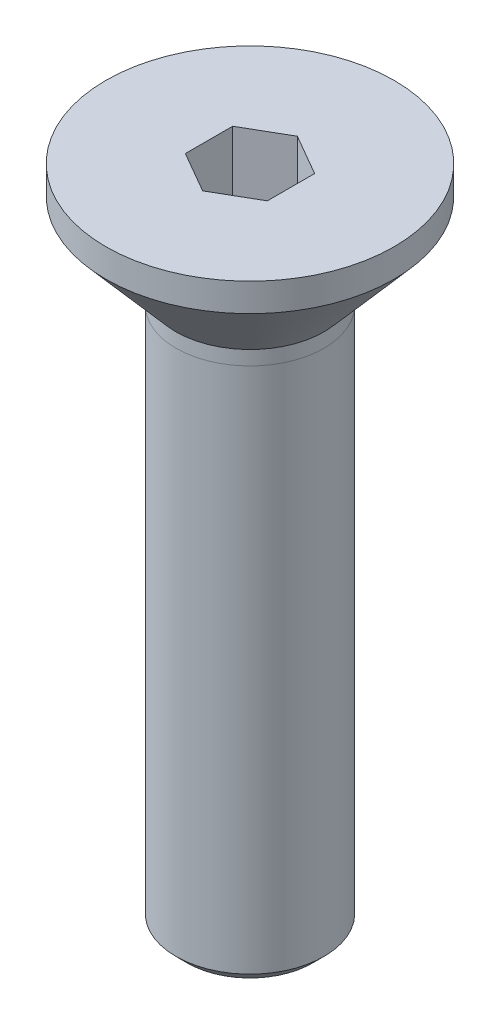
SolidWorks part; units mm, degrees
material "SS 18-8"
ref_plane "Front" through (0, 0, 0) normal (0, 0, 1) x (1, 0, 0)
ref_plane "Top" through (0, 0, 0) normal (0, 1, 0) x (1, 0, 0)
ref_plane "Right" through (0, 0, 0) normal (1, 0, 0) x (0, 0, -1)
sketch "Sketch1" plane through (0, 0, 0) normal (0, 0, 1) x (1, 0, 0)
  line L0 (0, 0) -> (0, -12.7)
  line L1 (0, -12.7) -> (1.2036, -12.7)
  line L2 (1.2036, -12.7) -> (1.4224, -12.4812)
  line L3 (1.4224, -12.4812) -> (1.4224, -2.0892)
  line L4 (0, 0) -> (2.7686, 0)
  line L5 (2.7686, 0) -> (2.7686, -0.5406)
  line L6 (2.7686, -0.5406) -> (1.4224, -2.0892)
  line L7 (2.7686, -0.5406) -> (3.2385, 0) construction
  line L8 (0, 0) -> (0, -25.4) construction
  line L9 (3.2385, 0) -> (2.7686, 0) construction
  dimension "D1" = 45
  dimension "E" = 2.8448
  dimension "A" = 6.477
  dimension "D2" = 41
  dimension "D3" = 0.2188
  dimension "Am" = 5.5372
  dimension "Length" = 12.7
revolve "Revolve1" add sketch "Sketch1" angle 360 about L8
sketch "Sketch2" plane through (0, 0, 0) normal (0, 1, 0) x (1, 0, 0)
  line L1 (0, 0.9092) -> (-0.7874, 0.4546)
  line L2 (-0.7874, 0.4546) -> (-0.7874, -0.4546)
  line L3 (-0.7874, -0.4546) -> (0, -0.9092)
  line L4 (0, -0.9092) -> (0.7874, -0.4546)
  line L5 (0.7874, -0.4546) -> (0.7874, 0.4546)
  line L6 (0.7874, 0.4546) -> (0, 0.9092)
  circle A0 centre (0, 0) radius 0.7874 construction
  dimension "J" = 1.5748
extrude "Extrude1" cut sketch "Sketch2" against normal blind 1.397
ref_plane "Plane1" through (0, -2.3622, 0) normal (0, 1, 0) x (-1, 0, 0)
split line "Split Line1"
equation "\"D3@Sketch1\" = \"E@Sketch1\"/13"
